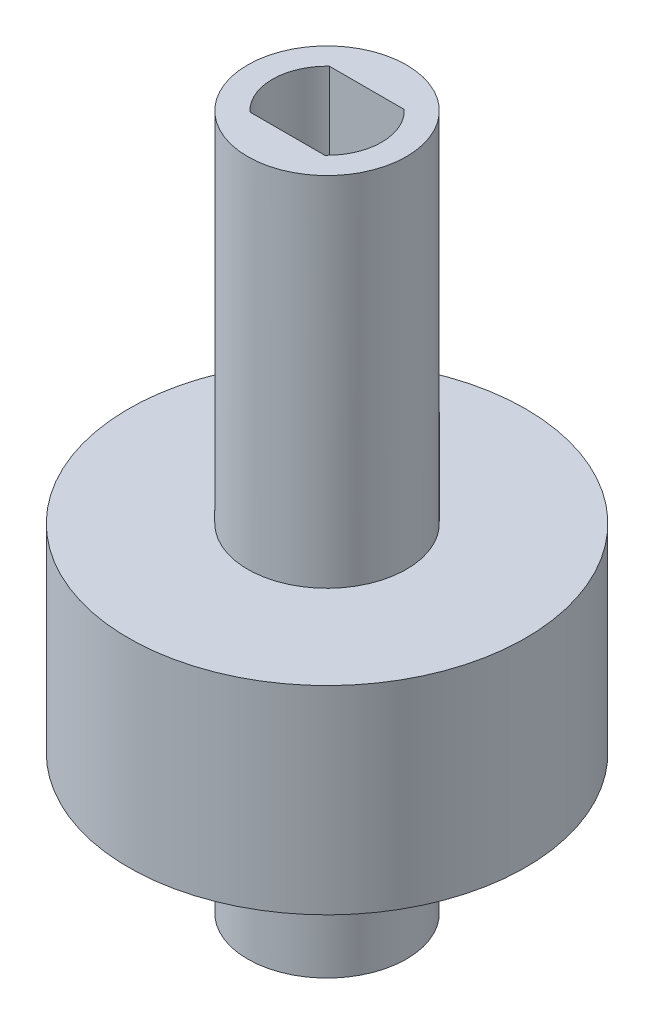
SolidWorks part; units mm, degrees
ref_plane "Front Plane" through (0, 0, 0) normal (0, 0, 1) x (1, 0, 0)
ref_plane "Top Plane" through (0, 0, 0) normal (0, 1, 0) x (1, 0, 0)
ref_plane "Right Plane" through (0, 0, 0) normal (1, 0, 0) x (0, 0, -1)
sketch "Sketch1" plane through (0, 0, 0) normal (0, 1, 0) x (1, 0, 0)
  circle A0 centre (0, 0) radius 4
  dimension "D1" = 8
extrude "Boss-Extrude1" add sketch "Sketch1" along normal blind 35
sketch "Sketch2" plane through (0, 35, 0) normal (0, 1, 0) x (1, 0, 0)
  line L1 (-1.8875, 2) -> (1.8875, 2)
  line L3 (-1.8875, -2) -> (1.8875, -2)
  line L5 (-1.8875, 2) -> (1.8875, -2) construction
  line L6 (-1.8875, -2) -> (1.8875, 2) construction
  arc A0 (-1.8875, 2) -> (-1.8875, -2) centre (0, 0) ccw
  arc A1 (1.8875, -2) -> (1.8875, 2) centre (0, 0) ccw
  point P0 (0, 0)
  dimension "D1" = 5.5
  dimension "D2" = 4
extrude "Cut-Extrude1" cut sketch "Sketch2" against normal blind 10
sketch "Sketch3" plane through (0, 0, 0) normal (0, -1, 0) x (-1, 0, 0)
  circle A0 centre (0, 0) radius 2.4
  dimension "D1" = 4.8
extrude "Cut-Extrude2" cut sketch "Sketch3" against normal blind 15
sketch "Sketch4" plane through (0, 0, 0) normal (0, -1, 0) x (1, 0, 0)
  circle A0 centre (0, 0) radius 10
  circle A1 centre (0, 0) radius 4
  dimension "D1" = 20
extrude "Boss-Extrude2" add sketch "Sketch4" against normal blind 10 from offset 7
